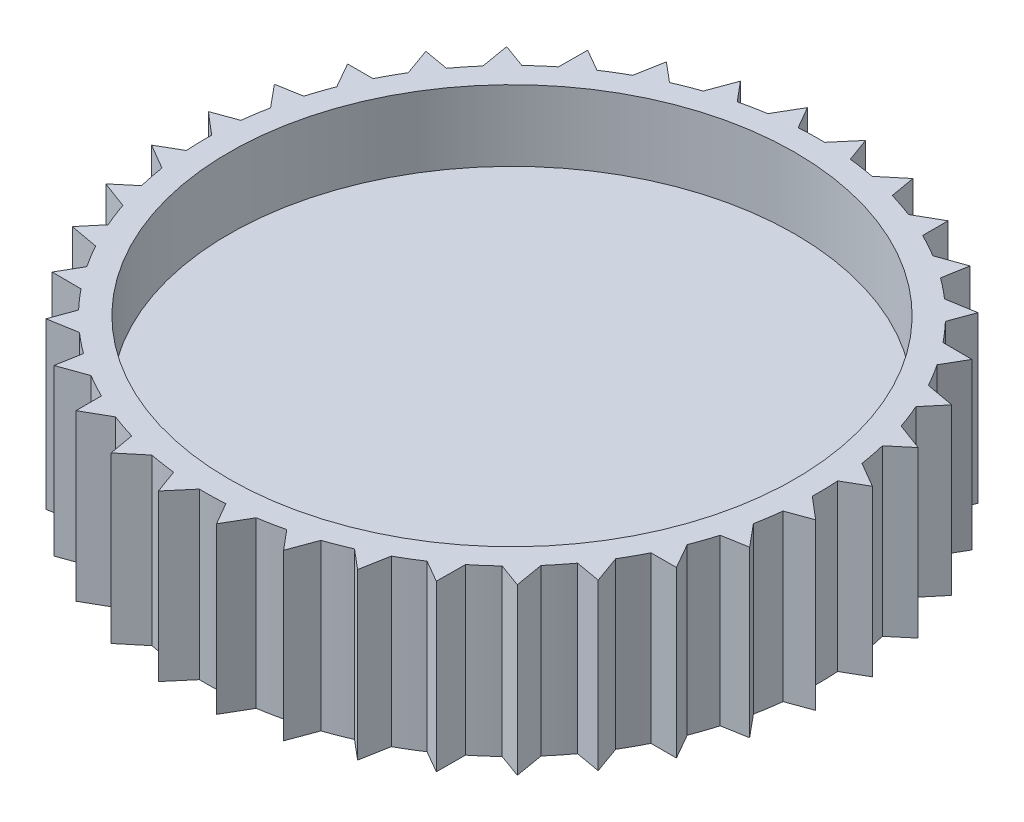
SolidWorks part; units mm, degrees
ref_plane "Front Plane" through (0, 0, 0) normal (0, 0, 1) x (1, 0, 0)
ref_plane "Top Plane" through (0, 0, 0) normal (0, 1, 0) x (1, 0, 0)
ref_plane "Right Plane" through (0, 0, 0) normal (1, 0, 0) x (0, 0, -1)
other "Configuration Table"
sketch "草图1" plane through (0, 0, 0) normal (0, 1, 0) x (1, 0, 0)
  circle A0 centre (0, 0) radius 13
  dimension "D1" = 26
extrude "凸台-拉伸1" add sketch "草图1" along normal blind 7
sketch "草图2" plane through (0, 7, 0) normal (0, 1, 0) x (1, 0, 0)
  circle A0 centre (0, 0) radius 12
  dimension "D1" = 24
extrude "切除-拉伸1" cut sketch "草图2" against normal blind 3
sketch "草图3" plane through (0, 7, 0) normal (0, 1, 0) x (1, 0, 0)
  line L0 (-12.1237, 4.6922) -> (-11.0446, 4.6922)
  line L1 (-12.1237, 4.6922) -> (-12.7329, 5.7609)
  line L2 (-11.0446, 4.6922) -> (-11.6538, 5.7609)
  line L3 (-12.7329, 5.7609) -> (-11.6538, 5.7609)
  line L4 (-11.1247, 6.7262) -> (-10.062, 6.5388)
  line L5 (-11.1247, 6.7262) -> (-11.5391, 7.8844)
  line L6 (-11.5391, 7.8844) -> (-10.4764, 7.6971)
  line L7 (-10.062, 6.5388) -> (-10.4764, 7.6971)
  line L8 (-9.7877, 8.5558) -> (-8.7737, 8.1867)
  line L9 (-9.7877, 8.5558) -> (-9.9947, 9.7684)
  line L10 (-9.9947, 9.7684) -> (-8.9807, 9.3993)
  line L11 (-8.7737, 8.1867) -> (-8.9807, 9.3993)
  line L12 (-8.1533, 10.1254) -> (-7.2188, 9.5859)
  line L13 (-8.1533, 10.1254) -> (-8.1465, 11.3556)
  line L14 (-8.1465, 11.3556) -> (-7.2121, 10.816)
  line L15 (-7.2188, 9.5859) -> (-7.2121, 10.816)
  line L16 (-6.2712, 11.3874) -> (-5.4446, 10.6938)
  line L17 (-6.2712, 11.3874) -> (-6.0509, 12.5977)
  line L18 (-6.0509, 12.5977) -> (-5.2243, 11.9041)
  line L19 (-5.4446, 10.6938) -> (-5.2243, 11.9041)
  line L20 (-4.1985, 12.3034) -> (-3.5049, 11.4767)
  line L21 (-4.1985, 12.3034) -> (-3.7714, 13.457)
  line L22 (-3.7714, 13.457) -> (-3.0778, 12.6304)
  line L23 (-3.5049, 11.4767) -> (-3.0778, 12.6304)
  line L24 (-1.9983, 12.8455) -> (-1.4587, 11.911)
  line L25 (-1.9983, 12.8455) -> (-1.3773, 13.9075)
  line L26 (-1.3773, 13.9075) -> (-0.8378, 12.973)
  line L27 (-1.4587, 11.911) -> (-0.8378, 12.973)
  line L28 (0.2627, 12.9973) -> (0.6317, 11.9834)
  line L29 (0.2627, 12.9973) -> (1.0586, 13.9354)
  line L30 (1.0586, 13.9354) -> (1.4277, 12.9214)
  line L31 (0.6317, 11.9834) -> (1.4277, 12.9214)
  line L32 (2.5157, 12.7543) -> (2.703, 11.6916)
  line L33 (2.5157, 12.7543) -> (3.4624, 13.5398)
  line L34 (3.4624, 13.5398) -> (3.6497, 12.4772)
  line L35 (2.703, 11.6916) -> (3.6497, 12.4772)
  line L36 (4.6922, 12.1237) -> (4.6922, 11.0446)
  line L37 (4.6922, 12.1237) -> (5.7609, 12.7329)
  line L38 (5.7609, 12.7329) -> (5.7609, 11.6538)
  line L39 (4.6922, 11.0446) -> (5.7609, 11.6538)
  line L40 (6.7262, 11.1247) -> (6.5388, 10.062)
  line L41 (6.7262, 11.1247) -> (7.8844, 11.5391)
  line L42 (7.8844, 11.5391) -> (7.6971, 10.4764)
  line L43 (6.5388, 10.062) -> (7.6971, 10.4764)
  line L44 (8.5558, 9.7877) -> (8.1867, 8.7737)
  line L45 (8.5558, 9.7877) -> (9.7684, 9.9947)
  line L46 (9.7684, 9.9947) -> (9.3993, 8.9807)
  line L47 (8.1867, 8.7737) -> (9.3993, 8.9807)
  line L48 (10.1254, 8.1533) -> (9.5859, 7.2188)
  line L49 (10.1254, 8.1533) -> (11.3556, 8.1465)
  line L50 (11.3556, 8.1465) -> (10.816, 7.2121)
  line L51 (9.5859, 7.2188) -> (10.816, 7.2121)
  line L52 (11.3874, 6.2712) -> (10.6938, 5.4446)
  line L53 (11.3874, 6.2712) -> (12.5977, 6.0509)
  line L54 (12.5977, 6.0509) -> (11.9041, 5.2243)
  line L55 (10.6938, 5.4446) -> (11.9041, 5.2243)
  line L56 (12.3034, 4.1985) -> (11.4767, 3.5049)
  line L57 (12.3034, 4.1985) -> (13.457, 3.7714)
  line L58 (13.457, 3.7714) -> (12.6304, 3.0778)
  line L59 (11.4767, 3.5049) -> (12.6304, 3.0778)
  line L60 (12.8455, 1.9983) -> (11.911, 1.4587)
  line L61 (12.8455, 1.9983) -> (13.9075, 1.3773)
  line L62 (13.9075, 1.3773) -> (12.973, 0.8378)
  line L63 (11.911, 1.4587) -> (12.973, 0.8378)
  line L64 (12.9973, -0.2627) -> (11.9834, -0.6317)
  line L65 (12.9973, -0.2627) -> (13.9354, -1.0586)
  line L66 (13.9354, -1.0586) -> (12.9214, -1.4277)
  line L67 (11.9834, -0.6317) -> (12.9214, -1.4277)
  line L68 (12.7543, -2.5157) -> (11.6916, -2.703)
  line L69 (12.7543, -2.5157) -> (13.5398, -3.4624)
  line L70 (13.5398, -3.4624) -> (12.4772, -3.6497)
  line L71 (11.6916, -2.703) -> (12.4772, -3.6497)
  line L72 (12.1237, -4.6922) -> (11.0446, -4.6922)
  line L73 (12.1237, -4.6922) -> (12.7329, -5.7609)
  line L74 (12.7329, -5.7609) -> (11.6538, -5.7609)
  line L75 (11.0446, -4.6922) -> (11.6538, -5.7609)
  line L76 (11.1247, -6.7262) -> (10.062, -6.5388)
  line L77 (11.1247, -6.7262) -> (11.5391, -7.8844)
  line L78 (11.5391, -7.8844) -> (10.4764, -7.6971)
  line L79 (10.062, -6.5388) -> (10.4764, -7.6971)
  line L80 (9.7877, -8.5558) -> (8.7737, -8.1867)
  line L81 (9.7877, -8.5558) -> (9.9947, -9.7684)
  line L82 (9.9947, -9.7684) -> (8.9807, -9.3993)
  line L83 (8.7737, -8.1867) -> (8.9807, -9.3993)
  line L84 (8.1533, -10.1254) -> (7.2188, -9.5859)
  line L85 (8.1533, -10.1254) -> (8.1465, -11.3556)
  line L86 (8.1465, -11.3556) -> (7.2121, -10.816)
  line L87 (7.2188, -9.5859) -> (7.2121, -10.816)
  line L88 (6.2712, -11.3874) -> (5.4446, -10.6938)
  line L89 (6.2712, -11.3874) -> (6.0509, -12.5977)
  line L90 (6.0509, -12.5977) -> (5.2243, -11.9041)
  line L91 (5.4446, -10.6938) -> (5.2243, -11.9041)
  line L92 (4.1985, -12.3034) -> (3.5049, -11.4767)
  line L93 (4.1985, -12.3034) -> (3.7714, -13.457)
  line L94 (3.7714, -13.457) -> (3.0778, -12.6304)
  line L95 (3.5049, -11.4767) -> (3.0778, -12.6304)
  line L96 (1.9983, -12.8455) -> (1.4587, -11.911)
  line L97 (1.9983, -12.8455) -> (1.3773, -13.9075)
  line L98 (1.3773, -13.9075) -> (0.8378, -12.973)
  line L99 (1.4587, -11.911) -> (0.8378, -12.973)
  line L100 (-0.2627, -12.9973) -> (-0.6317, -11.9834)
  line L101 (-0.2627, -12.9973) -> (-1.0586, -13.9354)
  line L102 (-1.0586, -13.9354) -> (-1.4277, -12.9214)
  line L103 (-0.6317, -11.9834) -> (-1.4277, -12.9214)
  line L104 (-2.5157, -12.7543) -> (-2.703, -11.6916)
  line L105 (-2.5157, -12.7543) -> (-3.4624, -13.5398)
  line L106 (-3.4624, -13.5398) -> (-3.6497, -12.4772)
  line L107 (-2.703, -11.6916) -> (-3.6497, -12.4772)
  line L108 (-4.6922, -12.1237) -> (-4.6922, -11.0446)
  line L109 (-4.6922, -12.1237) -> (-5.7609, -12.7329)
  line L110 (-5.7609, -12.7329) -> (-5.7609, -11.6538)
  line L111 (-4.6922, -11.0446) -> (-5.7609, -11.6538)
  line L112 (-6.7262, -11.1247) -> (-6.5388, -10.062)
  line L113 (-6.7262, -11.1247) -> (-7.8844, -11.5391)
  line L114 (-7.8844, -11.5391) -> (-7.6971, -10.4764)
  line L115 (-6.5388, -10.062) -> (-7.6971, -10.4764)
  line L116 (-8.5558, -9.7877) -> (-8.1867, -8.7737)
  line L117 (-8.5558, -9.7877) -> (-9.7684, -9.9947)
  line L118 (-9.7684, -9.9947) -> (-9.3993, -8.9807)
  line L119 (-8.1867, -8.7737) -> (-9.3993, -8.9807)
  line L120 (-10.1254, -8.1533) -> (-9.5859, -7.2188)
  line L121 (-10.1254, -8.1533) -> (-11.3556, -8.1465)
  line L122 (-11.3556, -8.1465) -> (-10.816, -7.2121)
  line L123 (-9.5859, -7.2188) -> (-10.816, -7.2121)
  line L124 (-11.3874, -6.2712) -> (-10.6938, -5.4446)
  line L125 (-11.3874, -6.2712) -> (-12.5977, -6.0509)
  line L126 (-12.5977, -6.0509) -> (-11.9041, -5.2243)
  line L127 (-10.6938, -5.4446) -> (-11.9041, -5.2243)
  line L128 (-12.3034, -4.1985) -> (-11.4767, -3.5049)
  line L129 (-12.3034, -4.1985) -> (-13.457, -3.7714)
  line L130 (-13.457, -3.7714) -> (-12.6304, -3.0778)
  line L131 (-11.4767, -3.5049) -> (-12.6304, -3.0778)
  line L132 (-12.8455, -1.9983) -> (-11.911, -1.4587)
  line L133 (-12.8455, -1.9983) -> (-13.9075, -1.3773)
  line L134 (-13.9075, -1.3773) -> (-12.973, -0.8378)
  line L135 (-11.911, -1.4587) -> (-12.973, -0.8378)
  line L136 (-12.9973, 0.2627) -> (-11.9834, 0.6317)
  line L137 (-12.9973, 0.2627) -> (-13.9354, 1.0586)
  line L138 (-13.9354, 1.0586) -> (-12.9214, 1.4277)
  line L139 (-11.9834, 0.6317) -> (-12.9214, 1.4277)
  line L140 (-12.7543, 2.5157) -> (-11.6916, 2.703)
  line L141 (-12.7543, 2.5157) -> (-13.5398, 3.4624)
  line L142 (-13.5398, 3.4624) -> (-12.4772, 3.6497)
  line L143 (-11.6916, 2.703) -> (-12.4772, 3.6497)
  line L144 (-11.6538, 5.7609) -> (-12.1237, 4.6922) construction
  circle A0 centre (0, 0) radius 13 construction
  circle A1 centre (0, 0) radius 12 construction
  point P151 (0, 0)
  dimension "D1" = 36
extrude "凸台-拉伸2" add sketch "草图3" against normal through all
